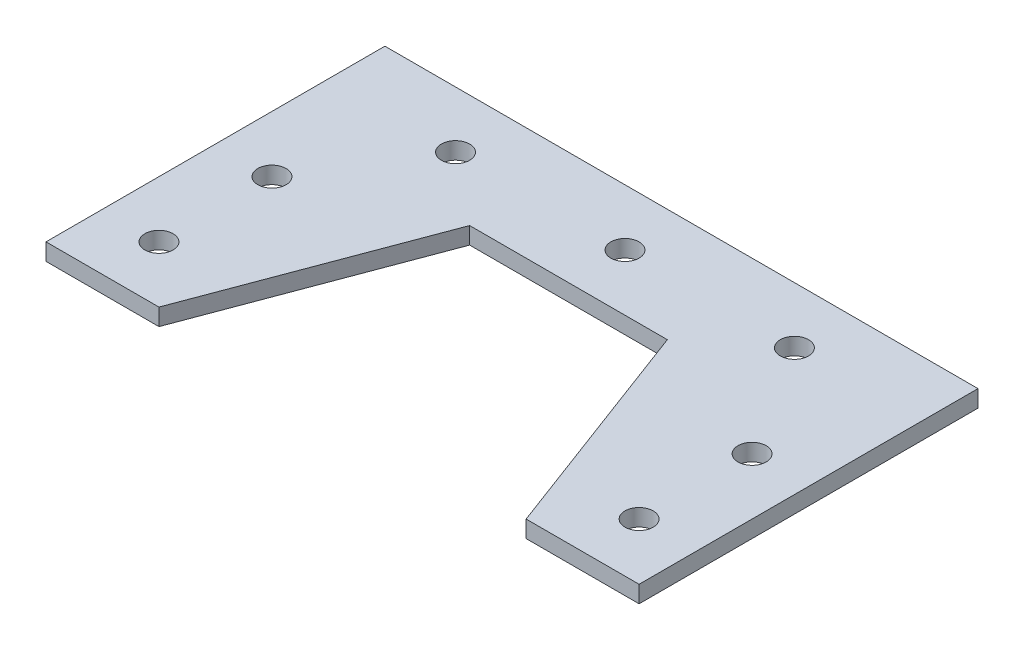
SolidWorks part; units mm, degrees
material "1060 Alloy"
ref_plane "Front Plane" through (0, 0, 0) normal (0, 0, 1) x (1, 0, 0)
ref_plane "Top Plane" through (0, 0, 0) normal (0, 1, 0) x (1, 0, 0)
ref_plane "Right Plane" through (0, 0, 0) normal (1, 0, 0) x (0, 0, -1)
sketch "Sketch1" plane through (0, 0, 0) normal (0, 1, 0) x (1, 0, 0)
  line L0 (-52.5, 20) -> (52.5, 20)
  line L1 (52.5, 20) -> (52.5, -40)
  line L2 (52.5, -40) -> (32.5, -40)
  line L3 (32.5, -40) -> (17.5, 0)
  line L4 (17.5, 0) -> (-17.5, 0)
  line L5 (-17.5, 0) -> (-32.5, -40)
  line L6 (-32.5, -40) -> (-52.5, -40)
  line L7 (-52.5, -40) -> (-52.5, 20)
  point P2 (0, 0)
  dimension "D1" = 105
  dimension "D2" = 35
  dimension "D3" = 20
  dimension "D4" = 20
  dimension "D5" = 60
  dimension "D6" = 20
extrude "Boss-Extrude1" add sketch "Sketch1" along normal blind 3
sketch "Sketch2" plane through (0, 3, 0) normal (0, 1, 0) x (1, 0, 0)
  line L0 (52.5, -40) -> (52.5, 20) construction
  line L1 (32.5, -40) -> (52.5, -40) construction
  line L2 (-52.5, -40) -> (-32.5, -40) construction
  line L3 (-52.5, 20) -> (-52.5, -40) construction
  line L4 (52.5, 20) -> (-52.5, 20) construction
  circle A0 centre (42.5, -10) radius 2.5
  circle A1 centre (42.5, -30) radius 2.5
  circle A7 centre (-42.5, -30) radius 2.5
  circle A8 centre (0, 10) radius 2.5
  circle A9 centre (-42.5, -10) radius 2.5
  circle A10 centre (-30, 10) radius 2.5
  circle A11 centre (30, 10) radius 2.5
  dimension "D1" = 5
  dimension "D2" = 5
  dimension "D3" = 5
  dimension "D4" = 5
  dimension "D5" = 5
  dimension "D6" = 5
  dimension "D7" = 5
  dimension "D10" = 10
  dimension "D8" = 10
  dimension "D9" = 0
  dimension "D11" = 20
  dimension "D12" = 10
  dimension "D13" = 20
  dimension "D14" = 0
  dimension "D15" = 10
  dimension "D16" = 10
  dimension "D17" = 52.5
  dimension "D18" = 30
  dimension "D19" = 30
extrude "Cut-Extrude1" cut sketch "Sketch2" against normal up to surface (3 mm away) up to face at (0, 0, 15)
